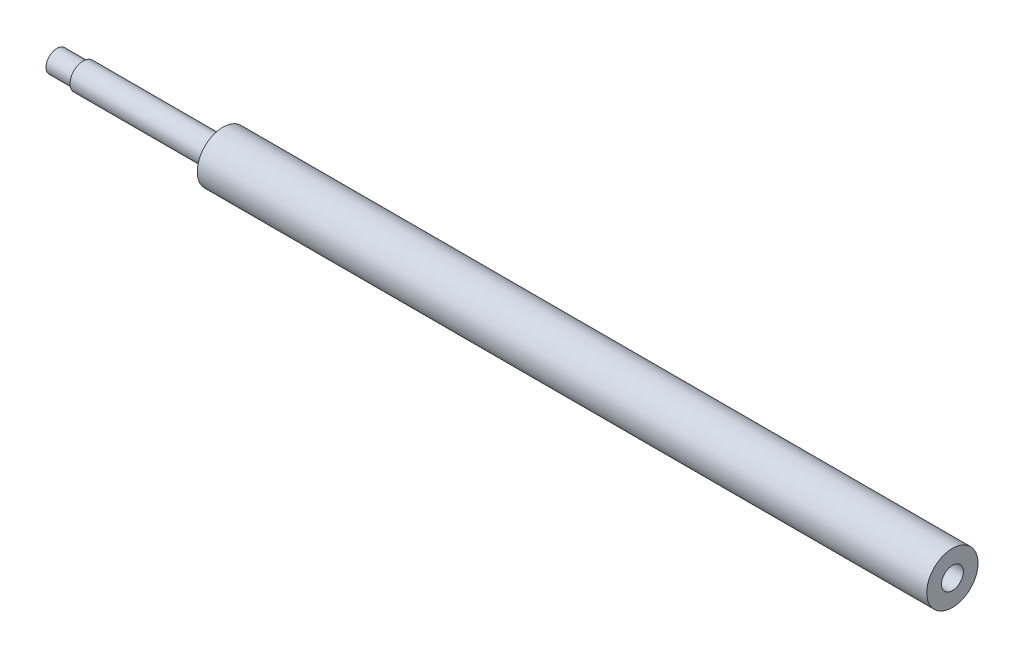
SolidWorks part; units mm, degrees
ref_plane "Plan1" through (0, 0, 0) normal (0, 0, 1) x (1, 0, 0)
ref_plane "Plan2" through (0, 0, 0) normal (0, 1, 0) x (1, 0, 0)
ref_plane "Plan3" through (0, 0, 0) normal (1, 0, 0) x (0, 0, -1)
sketch "Esquisse1" plane through (0, 0, 0) normal (0, 0, 1) x (1, 0, 0)
  line L0 (0, 0) -> (140, 0) construction
  line L1 (0, 0) -> (0, 2.5)
  line L2 (0, 2.5) -> (6, 2.5)
  line L3 (6, 2.5) -> (6, 3)
  line L4 (6, 3) -> (38, 3)
  line L7 (38, 3) -> (38, 5.875)
  line L8 (38, 5.875) -> (205, 5.875)
  line L9 (205, 5.875) -> (205, 0)
  line L10 (205, 0) -> (0, 0)
  dimension "D1" = 2.5
  dimension "D2" = 3
  dimension "D3" = 6
  dimension "D4" = 32
  dimension "D5" = 5.875
  dimension "D6" = 167
revolve "Base-Révolution" add sketch "Esquisse1" angle 360 about L0
ref_plane "Plan4" through (209, 0, 0) normal (1, 0, 0) x (0, 0, -1)
sketch "Esquisse6" plane through (209, 0, 0) normal (1, 0, 0) x (0, 0, -1)
  circle A0 centre (0, 0) radius 6
  circle A1 centre (0, 0) radius 5.875 construction
  dimension "D1" = 12
hole_wizard "Perçage1" positions "Esquisse8" profile "Esquisse7" hole size "M6" standard "ISO"
sketch "Esquisse8" plane through (205, 0, 0) normal (1, 0, 0) x (0, 0, -1)
  point P0 (0, 0)
sketch "Esquisse7" plane through (205, 0, 0) normal (0, 1, 0) x (0, 0, -1)
  line L0 (0, 0) -> (0, 21.5022)
  line L1 (0, 21.5022) -> (2.5, 20)
  line L2 (2.5, 20) -> (2.5, 0)
  line L5 (2.5, 0) -> (0, 0)
  line L10 (0, 21.5022) -> (-2.5, 20) construction
  line L11 (0, -6.35) -> (0, 107.95) construction
  dimension "Diamètre du perçage" = 5
  dimension "Profondeur du perçage" = 20
  dimension "Angle de pointe" = 118
sketch "Esquisse9" plane through (0, 0, 0) normal (0, 1, 0) x (1, 0, 0)
  point P0 (171.7942, 0)
